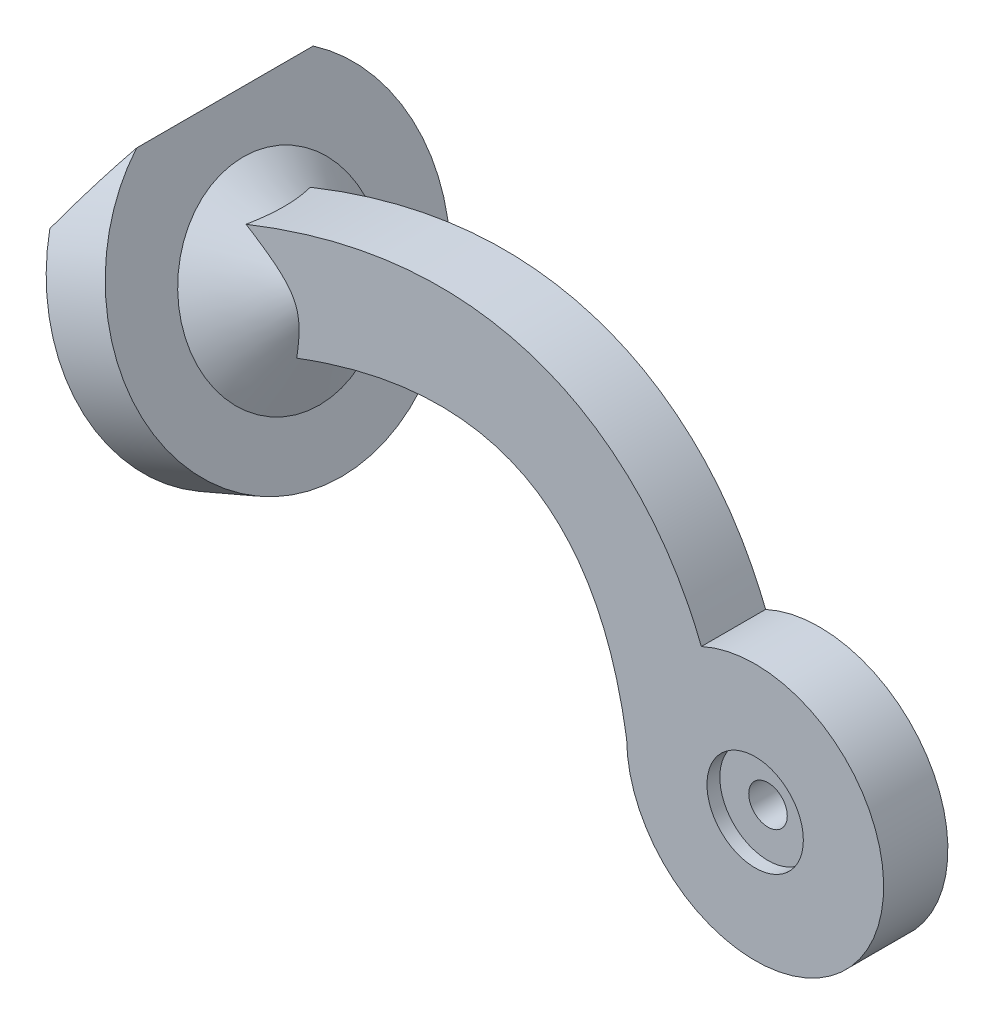
SolidWorks part; units mm, degrees
ref_plane "Front Plane" through (0, 0, 0) normal (0, 0, 1) x (1, 0, 0)
ref_plane "Top Plane" through (0, 0, 0) normal (0, 1, 0) x (1, 0, 0)
ref_plane "Right Plane" through (0, 0, 0) normal (1, 0, 0) x (0, 0, -1)
sketch "Sketch1" plane through (0, 0, 0) normal (0, 0, 1) x (1, 0, 0)
  circle A0 centre (0, 0) radius 10
  circle A1 centre (0, 0) radius 10 construction
extrude "Boss-Extrude1" add sketch "Sketch1" along normal blind 5
sketch "Sketch2" plane through (0, 0, 0) normal (0, 0, -1) x (-1, 0, 0)
  line L0 (38.0644, 11.8065) -> (41.2212, 19.1601)
  line L1 (41.2212, 19.1601) -> (41.2147, 19.1601)
  line L2 (1.7331, -1.652) -> (9.6918, -2.4635)
  circle A0 centre (0, 0) radius 10 construction
  spline S0 degree 2 poles (9.6918, -2.4635) (12.2737, 22.8551) (38.0644, 11.8065) knots 0 0 0 1 1 1
  spline S1 degree 1 poles (1.7331, -1.652) (41.2147, 19.1601) knots 0 0 1 1 construction
  spline S2 degree 3 poles (1.7331, -1.652) (1.795, -1.0444) (1.9402, 0.1787) (2.3061, 2.5342) (2.9184, 5.3699) (3.9316, 8.5905) (5.708, 12.6407) (8.8586, 17.2072) (14.3185, 21.2628) (20.7552, 23.203) (26.2761, 23.2473) (30.7491, 22.5736) (34.1531, 21.746) (37.0521, 20.8058) (39.4093, 19.9142) (40.6189, 19.4153) (41.2147, 19.1601) knots 0 0 0 0 0.03125 0.0625 0.125 0.1875 0.25 0.375 0.5 0.625 0.75 0.8125 0.875 0.9375 0.96875 1 1 1 1
  dimension "D1" = 8
extrude "Boss-Extrude2" add sketch "Sketch2" against normal blind 5
sketch "Sketch3" plane through (-27.8617, -11.9605, 0) normal (-0.9189, -0.3945, 0) x (0, 0, 1)
  line L0 (5, 25.8643) -> (5, 33.8669) construction
  line L2 (5, 25.8643) -> (0, 25.8643) construction
  circle A0 centre (2.5, 29.8656) radius 12.5
  point P9 (5, 29.8656)
  point P10 (2.5, 25.8643)
  dimension "D1" = 25
extrude "Boss-Extrude3" add sketch "Sketch3" along normal blind 5
ref_plane "Plane1" through (0, 0, 15) normal (0, 0, 1) x (1, 0, 0)
sketch "Sketch5" plane through (-27.8617, -11.9605, 0) normal (0.9189, 0.3945, 0) x (0, 0, -1)
  circle A2 centre (-2.5, 29.1949) radius 7.5
  dimension "D1" = 15
extrude "Boss-Extrude4" add sketch "Sketch5" along normal blind 5 draft 52
ref_plane "Plane2" through (0, 0, -10) normal (0, 0, -1) x (-1, 0, 0)
sketch "Sketch12" plane through (0, 0, -10) normal (0, 0, -1) x (-1, 0, 0)
  line L0 (48.6938, 16.9617) -> (42.4398, 27.2594)
  line L1 (48.6938, 16.9617) -> (52.5454, 36.3098)
  line L2 (52.5454, 36.3098) -> (42.4398, 27.2594)
extrude "Cut-Extrude5" cut sketch "Sketch12" against normal blind 30
sketch "Sketch13" plane through (-32.4563, -13.9328, 0) normal (-0.9189, -0.3945, 0) x (0, 0, 1)
  line L1 (12.9372, 36.7442) -> (-7.9372, 36.7442)
  line L2 (12.9372, 36.7442) -> (-7.9372, 36.7442)
  arc A1 (-7.9372, 36.7442) -> (12.9372, 36.7442) centre (2.5, 29.8656) ccw
  arc A2 (-7.9372, 36.7442) -> (12.9372, 36.7442) centre (2.5, 29.8656) ccw
  dimension "D1" = 0
extrude "Boss-Extrude5" add sketch "Sketch13" along normal blind 10 draft 47
sketch "Sketch14" plane through (0, 0, 5) normal (0, 0, 1) x (1, 0, 0)
  circle A1 centre (0, 0) radius 3.75
  dimension "D1" = 7.5
  dimension "D3" = 10
  dimension "D2" = 9.0818
extrude "Cut-Extrude6" cut sketch "Sketch14" against normal blind 1
sketch "Sketch15" plane through (0, 0, 0) normal (0, 0, -1) x (-1, 0, 0)
  circle A0 centre (0, 0) radius 1.5
  arc A1 (4.1858, 9.0818) -> (9.9997, -0.0749) centre (0, 0) ccw construction
  dimension "D1" = 3
extrude "Cut-Extrude7" cut sketch "Sketch15" against normal blind 10
